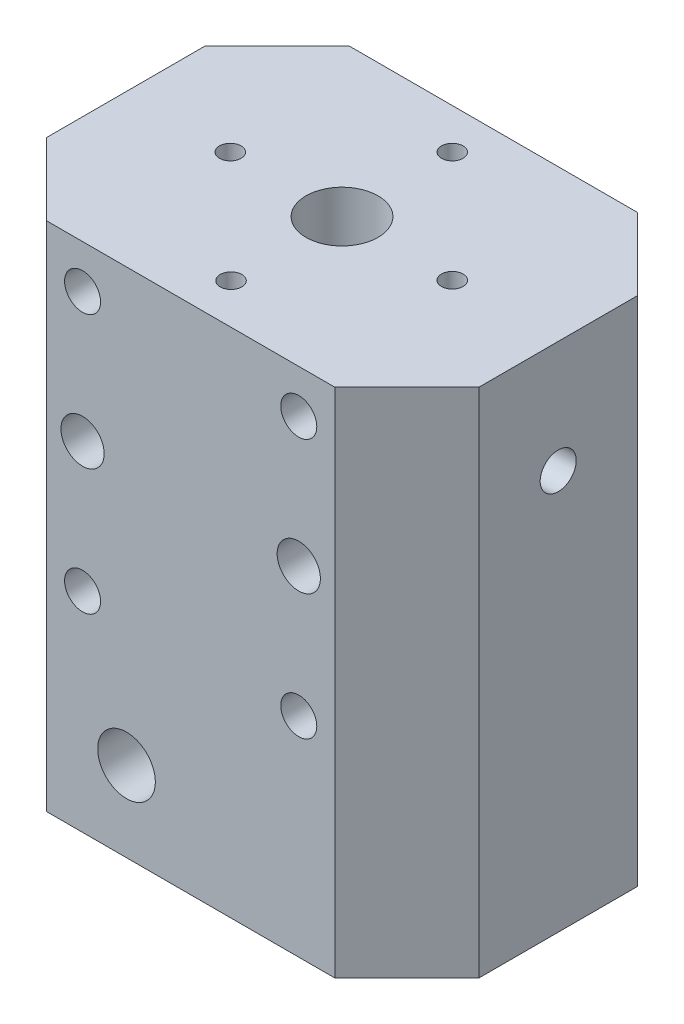
SolidWorks part; units mm, degrees
ref_plane "Front Plane" through (0, 0, 0) normal (0, 0, 1) x (1, 0, 0)
ref_plane "Top Plane" through (0, 0, 0) normal (0, 1, 0) x (1, 0, 0)
ref_plane "Right Plane" through (0, 0, 0) normal (1, 0, 0) x (0, 0, -1)
sketch "Sketch1" plane through (0, 0, 0) normal (0, 0, 1) x (1, 0, 0)
  line L0 (0, 0) -> (5, 0) construction
  line L1 (5, 11.25) -> (5, 0) construction
  line L2 (0.05, 0) -> (5, 11.25) construction
  line L3 (0, 0) -> (0, 82) construction
  line L4 (0.05, 0) -> (5, 11.25)
  line L5 (5, 11.25) -> (5, 82)
  line L6 (0, 82) -> (5, 82) construction
  line L9 (7.5, 11.25) -> (7.5, 82)
  line L10 (7.5, 11.25) -> (2.55, 0)
  line L11 (0.05, 0) -> (2.55, 0)
  line L12 (7.5, 82) -> (5, 82)
  dimension "D1" = 0.05
  dimension "D2" = 5
  dimension "D3" = 90
  dimension "D4" = 11.25
  dimension "D5" = 82
  dimension "D6" = 90
  dimension "D7" = 2.5
  dimension "D8" = 11.25
  dimension "D9" = 2.5
revolve "Revolve1" add sketch "Sketch1" angle 360 about L3
sketch "Sketch2" plane through (0, 82, 0) normal (0, 1, 0) x (1, 0, 0)
  line L0 (0, 0) -> (0, -21) construction
  line L1 (0, -21) -> (30, -21) construction
  line L2 (-7.5, 0) -> (-7.5, -21) construction
  line L3 (30, -21) -> (-30, -21)
  line L4 (30, -21) -> (30, 21)
  line L5 (30, 21) -> (-30, 21)
  line L6 (-30, -21) -> (-30, 21)
  line L7 (-5, 0) -> (-5, -21) construction
  circle A0 centre (0, 0) radius 7.5
  circle A1 centre (0, 0) radius 5 construction
  circle A2 centre (0, 0) radius 5 construction
  dimension "D1" = 15
  dimension "D2" = 30
extrude "Boss-Extrude1" add sketch "Sketch2" against normal blind 71
sketch "Sketch3" plane through (0, 0, 21) normal (0, 0, 1) x (1, 0, 0)
  line L0 (-30, 82) -> (-15, 82) construction
  line L1 (-30, 11) -> (-8.9, 11) construction
  line L2 (-30, 82) -> (30, 82) construction
  line L3 (-15, 82) -> (-15, 76) construction
  line L4 (-30, 11) -> (-30, 82) construction
  line L5 (-30, 11) -> (30, 11) construction
  line L6 (-8.9, 11) -> (-8.9, 22.1) construction
  line L7 (30, 82) -> (-30, 82) construction
  circle A0 centre (-15, 76) radius 2.5
  circle A1 centre (-15, 58) radius 3
  circle A2 centre (-15, 40) radius 2.5
  circle A3 centre (15, 76) radius 2.5
  circle A4 centre (15, 58) radius 3
  circle A5 centre (15, 40) radius 2.5
  circle A6 centre (-8.9, 22.1) radius 4
  dimension "D1" = 5
  dimension "D4" = 5
  dimension "D5" = 6
  dimension "D6" = 30
  dimension "D10" = 6.1
  dimension "D11" = 17.9
  dimension "D14" = 6
  dimension "D15" = 18
  dimension "D16" = 18
  dimension "D17" = 15
  dimension "D8" = 18
  dimension "D2" = 18
  dimension "D3" = 15
  dimension "D7" = 30
  dimension "D9" = 15
  dimension "D12" = 30
  dimension "D13" = 6
extrude "Cut-Extrude1" cut sketch "Sketch3" against normal through all
ref_plane "Plane1" through (0, 0, 0) normal (-0.9981, -0.0609, 0) x (0, 0, 1)
sketch "Sketch7" plane through (0, 0, 0) normal (-0.9981, -0.0609, 0) x (0, 0, 1)
  circle A0 centre (0, 64.5) radius 2.5
  dimension "D1" = 64.5
  dimension "D2" = 5
extrude "Cut-Extrude3" cut sketch "Sketch7" against normal blind 81
sketch "Sketch10" plane through (0, 0, 0) normal (0, -1, 0) x (1, 0, 0)
  circle A0 centre (0, 0) radius 0.05
  circle A1 centre (0, 0) radius 1.25
  dimension "D1" = 2.5
extrude "Boss-Extrude2" add sketch "Sketch10" along normal blind 8
chamfer "Chamfer10" distance 1 angle 45 1 edges at (0, -8, -1.25)
sketch "Sketch12" plane through (0, 82, 0) normal (0, 1, 0) x (1, 0, 0)
  line L0 (0, 0) -> (0, -21) construction
  line L1 (0, -21) -> (-21.1, -21) construction
  line L2 (30, -21) -> (-30, -21) construction
  line L3 (-21.1, -21) -> (-21.1, 21) construction
  line L4 (30, 21) -> (-30, 21) construction
  line L5 (-21.1, 21) -> (20.9, 21) construction
  line L6 (20.9, 21) -> (20.9, -21) construction
  line L7 (20.9, -21) -> (-21.1, -21) construction
  line L8 (0, -21) -> (0, -15.4) construction
  line L9 (-0.1, 21) -> (-0.1, 15.4) construction
  line L10 (-21.1, 0) -> (-15.5, 0) construction
  line L11 (20.9, 0) -> (15.3, 0) construction
  circle A0 centre (-15.5, 0) radius 1.5
  circle A1 centre (-0.1, 15.4) radius 1.5
  circle A2 centre (15.3, 0) radius 1.5
  circle A3 centre (0, -15.4) radius 1.5
extrude "Cut-Extrude5" cut sketch "Sketch12" against normal blind 5
chamfer "Chamfer11" distance 10 angle 45 4 edges at (30, 46.5, 21) (30, 46.5, -21) (-30, 46.5, -21) (-30, 46.5, 21)
